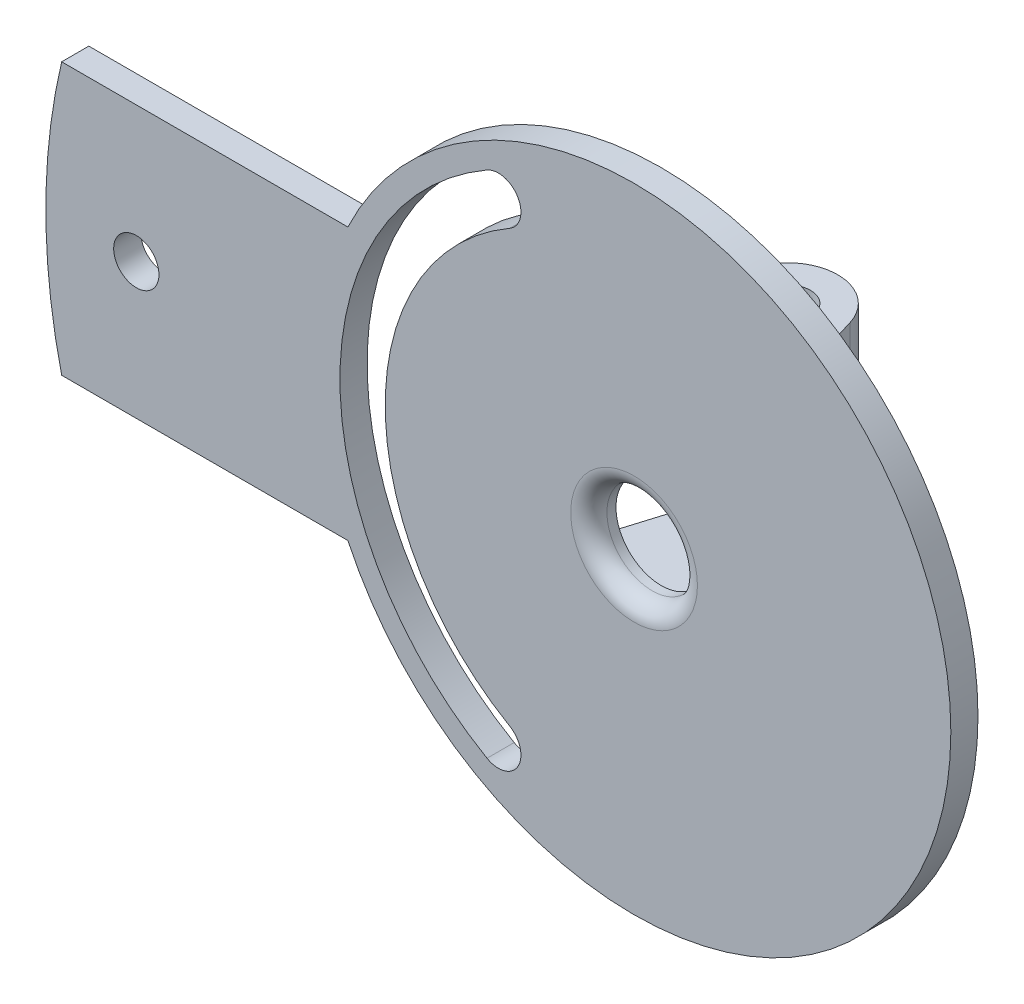
SolidWorks part; units mm, degrees
ref_plane "정면" through (0, 0, 0) normal (0, 0, 1) x (1, 0, 0)
ref_plane "윗면" through (0, 0, 0) normal (0, 1, 0) x (1, 0, 0)
ref_plane "우측면" through (0, 0, 0) normal (1, 0, 0) x (0, 0, -1)
sketch "스케치1" plane through (0, 0, 0) normal (0, 0, 1) x (1, 0, 0)
  line L0 (0, 65.3097) -> (0, -65.3097) construction
  line L1 (-109.2501, 0) -> (109.2501, 0) construction
  line L2 (15, 25.9808) -> (0, 0) construction
  line L3 (0, -15) -> (0, 15)
  line L4 (0, -15) -> (-63.2456, -15)
  line L5 (0, 15) -> (-63.2456, 15)
  circle A0 centre (0, 0) radius 5
  circle A1 centre (0, 0) radius 30 construction
  circle A2 centre (0, 0) radius 35
  circle A3 centre (0, 30) radius 2.5
  circle A18 centre (15, 25.9808) radius 2.5
  circle A19 centre (25.9808, 15) radius 2.5
  circle A20 centre (30, 0) radius 2.5
  circle A21 centre (25.9808, -15) radius 2.5
  circle A22 centre (15, -25.9808) radius 2.5
  circle A23 centre (0, -30) radius 2.5
  circle A24 centre (-15, -25.9808) radius 2.5
  circle A25 centre (-25.9808, -15) radius 2.5
  circle A26 centre (-30, 0) radius 2.5
  circle A27 centre (-25.9808, 15) radius 2.5
  circle A28 centre (-15, 25.9808) radius 2.5
  circle A29 centre (-55, 0) radius 2.5
  circle A30 centre (0, 0) radius 65
  circle A31 centre (0, 0) radius 32.5
  circle A32 centre (0, 0) radius 27.5
  point P5 (0, 0)
  point P6 (0, 0)
  point P15 (0, 0)
  point P39 (0, 0)
  point P44 (0, 0)
  dimension "D1" = 10
  dimension "D2" = 60
  dimension "D3" = 70
  dimension "D4" = 5
  dimension "D7" = 30
  dimension "D10" = 5
  dimension "D12" = 130
  dimension "D6" = 30
  dimension "D9" = 90
  dimension "D11" = 55
  dimension "D5" = 12
sketch "스케치3" plane through (0, 0, 0) normal (0, 1, 0) x (1, 0, 0)
  line L0 (-46.8932, 0) -> (33.9265, 0) construction
  line L1 (-109.2501, 0) -> (109.2501, 0) construction
  line L2 (27.5, 0) -> (32.5, 0) construction
  line L3 (0, -29.8322) -> (0, 29.8322) construction
  line L4 (-10, 0) -> (10, 0)
  line L5 (0, 0) -> (0, 14) construction
  line L6 (-10, 0) -> (-5.2626, 15.5983)
  line L7 (10, 0) -> (5.2626, 15.5983)
  circle A0 centre (0, 14) radius 2.5
  arc A2 (5.2626, 15.5983) -> (-5.2626, 15.5983) centre (0, 14) ccw
  point P6 (0, 0)
  point P10 (0, 0)
  dimension "D3" = 5
  dimension "D4" = 5.5
  dimension "D1" = 20
  dimension "D2" = 14
sketch "스케치4" plane through (0, 0, 0) normal (1, 0, 0) x (0, 0, -1)
  line L0 (0, -6) -> (0, 6)
  line L1 (0, 65.3097) -> (0, -65.3097) construction
  line L5 (0, -6) -> (25, -6)
  line L6 (25, -6) -> (25, 6)
  line L7 (25, 6) -> (0, 6)
  point P4 (0, 0)
  dimension "D1" = 12
  dimension "D2" = 25
extrude "보스-돌출1" add sketch "스케치1" along normal blind 3 contours L5 A30 L4 A2 A29 | A32 L5 L3 A0 L4 | L5 A32 L4 L3 A0 | A31 L4 A2 L5 | A31 L5 A2 L4 | A32 A24 A31 A23 | A23 | A32 A23 A31 A22 | A22 | A32 A22 A31 A21 | A21 | A32 A21 A31 A20 | A20 | A32 A20 A31 A19 | A19 | A32 A19 A31 A18 | A18 | A32 A18 A31 A3 | A3 | A32 A3 A31 A28 | A27
extrude "보스-돌출2" add sketch "스케치3" along normal mid plane 30
extrude "컷-돌출1" cut sketch "스케치4" against normal mid plane 20
fillet "필렛1" radius 2 1 edges at (5, 0, 3)
